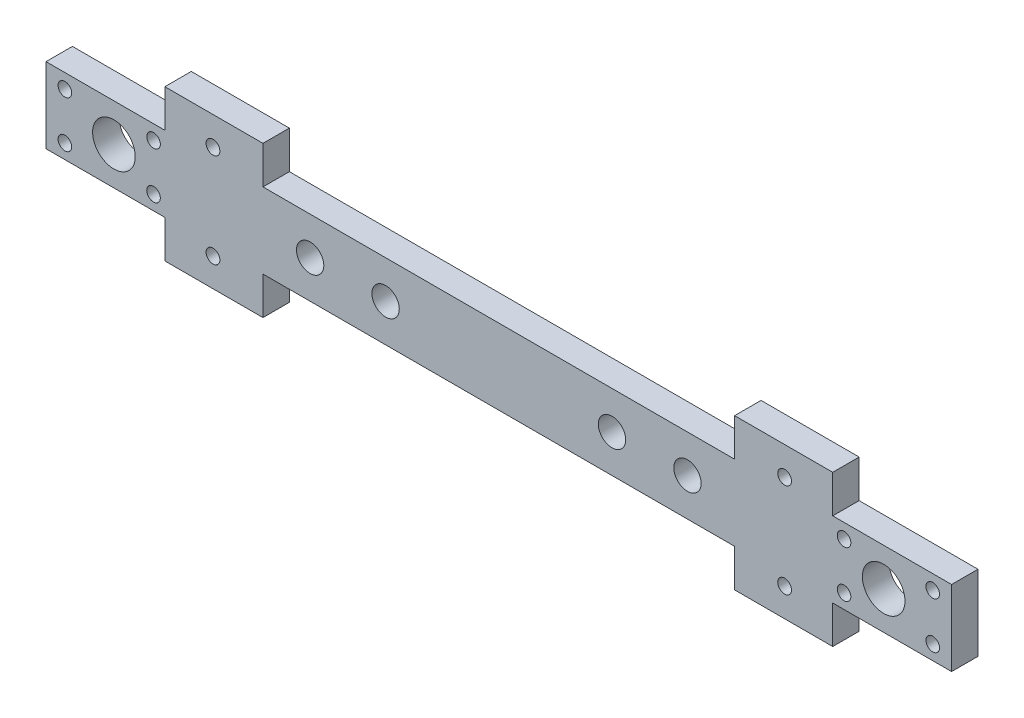
SolidWorks part; units mm, degrees
ref_plane "Alzado" through (0, 0, 0) normal (0, 0, 1) x (1, 0, 0)
ref_plane "Planta" through (0, 0, 0) normal (0, 1, 0) x (1, 0, 0)
ref_plane "Vista lateral" through (0, 0, 0) normal (1, 0, 0) x (0, 0, -1)
sketch "Sketch2" plane through (0, 0, 0) normal (0, 0, 1) x (1, 0, 0)
  line L0 (-56.9681, -20) -> (-56.9681, 20)
  line L1 (55, 0) -> (-55, 0) construction
  line L2 (-56.9681, 20) -> (6.0319, 20)
  line L3 (6.0319, 20) -> (6.0319, 40)
  line L4 (6.0319, 40) -> (58.0319, 40)
  line L5 (58.0319, 40) -> (58.0319, 20)
  line L6 (58.0319, 20) -> (308.0319, 20)
  line L7 (308.0319, 20) -> (308.0319, 40)
  line L8 (308.0319, 40) -> (360.0319, 40)
  line L9 (360.0319, 40) -> (360.0319, 20)
  line L10 (360.0319, 20) -> (423.0319, 20)
  line L11 (423.0319, 20) -> (423.0319, -20)
  line L13 (360.0319, -20) -> (423.0319, -20)
  line L14 (360.0319, -40) -> (360.0319, -20)
  line L15 (308.0319, -40) -> (360.0319, -40)
  line L16 (308.0319, -20) -> (308.0319, -40)
  line L17 (58.0319, -20) -> (308.0319, -20)
  line L18 (58.0319, -40) -> (58.0319, -20)
  line L19 (6.0319, -40) -> (58.0319, -40)
  line L20 (6.0319, -20) -> (6.0319, -40)
  line L21 (-56.9681, -20) -> (6.0319, -20)
  dimension "D1" = 40
  dimension "D2" = 63
  dimension "D3" = 52
  dimension "D4" = 63
  dimension "D5" = 52
  dimension "D6" = 40
  dimension "D7" = 40
  dimension "D8" = 80
  dimension "D9" = 80
  dimension "D10" = 480
extrude "Boss-Extrude1" add sketch "Sketch2" along normal blind 14
sketch "Sketch3" plane through (0, 0, 14) normal (0, 0, 1) x (1, 0, 0)
  line L0 (7.7, 0) -> (-7.7, 0) construction
  line L1 (-56.9681, 20) -> (-56.9681, -20) construction
  line L2 (58.0319, 20) -> (58.0319, 40) construction
  circle A0 centre (-20.9681, 0) radius 11.3
  circle A1 centre (-46.9681, 12.35) radius 3.6
  circle A2 centre (0.0319, 12.35) radius 3.6
  circle A3 centre (0.0319, -12.35) radius 3.6
  circle A4 centre (-46.9681, -12.35) radius 3.6
  circle A5 centre (31.5319, 25) radius 3.65
  circle A6 centre (31.5319, -25) radius 3.65
  circle A7 centre (83.0319, 0) radius 7.25
  circle A8 centre (123.0319, 0) radius 7.25
  circle A9 centre (283.0319, 0) radius 7.25
  circle A10 centre (243.0319, 0) radius 7.25
  circle A11 centre (334.5319, -25) radius 3.65
  circle A12 centre (334.5319, 25) radius 3.65
  circle A13 centre (366.0319, -12.35) radius 3.6
  circle A14 centre (366.0319, 12.35) radius 3.6
  circle A15 centre (387.0319, 0) radius 11.3
  circle A16 centre (413.0319, -12.35) radius 3.6
  circle A17 centre (413.0319, 12.35) radius 3.6
  dimension "D1" = 22.6
  dimension "D3" = 7.2
  dimension "D4" = 7.2
  dimension "D9" = 7.3
  dimension "D12" = 14.5
  dimension "D13" = 14.5
  dimension "D2" = 36
  dimension "D5" = 12.35
  dimension "D6" = 12.35
  dimension "D7" = 10
  dimension "D8" = 47
  dimension "D10" = 26.5
  dimension "D11" = 25
  dimension "D14" = 140
  dimension "D15" = 180
extrude "Cut-Extrude1" cut sketch "Sketch3" against normal blind 14
